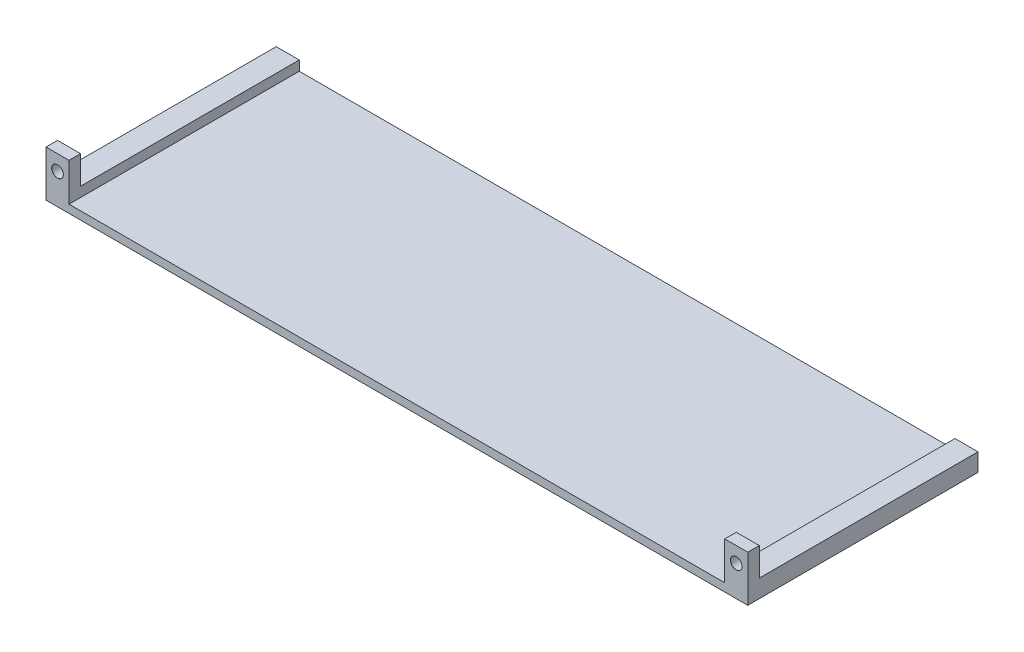
SolidWorks part; units mm, degrees
ref_plane "Front Plane" through (0, 0, 0) normal (0, 0, 1) x (1, 0, 0)
ref_plane "Top Plane" through (0, 0, 0) normal (0, 1, 0) x (1, 0, 0)
ref_plane "Right Plane" through (0, 0, 0) normal (1, 0, 0) x (0, 0, -1)
sketch "Sketch1" plane through (0, 0, 0) normal (0, 0, 1) x (1, 0, 0)
  line L0 (0, 0) -> (14.7224, 8.5)
  line L1 (0, 0) -> (0, -17)
  line L2 (0, 0) -> (-14.7224, 8.5)
  line L3 (0, 0) -> (0, -44.24)
  line L4 (-152.4, -44.24) -> (152.4, -44.24)
  line L5 (-152.4, -44.24) -> (-152.4, -24.8405)
  line L6 (0, -44.24) -> (0, -40.25)
  line L8 (-152.4, -44.24) -> (152.4, -44.24)
  line L9 (-152.4, -44.24) -> (-152.4, -40.74)
  line L10 (-152.4, -40.74) -> (152.4, -40.74)
  line L11 (152.4, -44.24) -> (152.4, -40.74)
  line L12 (-152.4, -40.74) -> (-142.4, -40.74)
  line L13 (-152.4, -40.74) -> (-152.4, -24.24)
  line L14 (-152.4, -24.24) -> (-142.4, -24.24)
  line L15 (-142.4, -40.74) -> (-142.4, -24.24)
  line L16 (152.4, -40.74) -> (142.4, -40.74)
  line L17 (152.4, -40.74) -> (152.4, -24.24)
  line L18 (152.4, -24.24) -> (142.4, -24.24)
  line L19 (142.4, -40.74) -> (142.4, -24.24)
  circle A0 centre (0, 0) radius 13.01
  circle A1 centre (0, 0) radius 17
  circle A2 centre (0, -17) radius 2.01
  circle A3 centre (14.7506, 8.5319) radius 2.01
  circle A4 centre (-14.9188, 8.588) radius 2.01
  circle A5 centre (0, 0) radius 40.25
  point P16 (0, -44.24)
  dimension "D1" = 26.02
  dimension "D2" = 34
  dimension "D3" = 4.02
  dimension "D8" = 80.5
  dimension "D4" = 120
  dimension "D5" = 120
  dimension "D6" = 44.24
  dimension "D7" = 304.8
  dimension "D9" = 3.5
  dimension "D10" = 10
  dimension "D11" = 10
  dimension "D12" = 16.5
  dimension "D13" = 16.5
extrude "Boss-Extrude1" add sketch "Sketch1" against normal blind 100 contours L10 L15 L14 L13 L5 | L10 L5 L4 L6 | L4 L11 L10 L6 | L19 L10 L17 L18
sketch "Sketch3" plane through (0, 0, 0) normal (0, 0, 1) x (1, 0, 0)
  line L0 (-142.4, -40.74) -> (-152.4, -40.74) construction
  line L1 (-152.4, -44.24) -> (-152.4, -24.24) construction
  line L2 (-142.4, -27.5127) -> (-152.4, -27.5127) construction
  line L3 (-142.4, -40.74) -> (-142.4, -24.24) construction
  line L4 (-147.4, -44.24) -> (-147.4, -37.5733)
  line L5 (-152.4, -44.24) -> (152.4, -44.24) construction
  line L6 (-147.4, -37.5733) -> (-147.4, -30.9067)
  line L7 (0, -40.25) -> (0, -44.24)
  line L8 (147.4, -44.24) -> (147.4, -37.5733)
  line L9 (147.4, -37.5733) -> (147.4, -30.9067)
  dimension "D1" = 6.6667
  dimension "D2" = 6.6667
hole_wizard "Ø5.0mm Dowel Hole3" positions "Sketch4" profile "Sketch6" hole size "Ø5.0" standard "ANSI Metric"
sketch "Sketch4" plane through (0, 0, 0) normal (0, 0, 1) x (1, 0, 0)
  point P0 (-147.4, -30.9067)
  point P3 (-147.4, -37.5733)
  point P6 (147.4, -30.9067)
  point P9 (147.4, -37.5733)
sketch "Sketch6" plane through (-147.4, -30.9067, 0) normal (1, 0, 0) x (0, -1, 0)
  line L0 (0, 0) -> (0, 101.5022)
  line L1 (0, 101.5022) -> (2.5, 100)
  line L2 (2.5, 100) -> (2.5, 0.025)
  line L3 (2.5, 0.025) -> (2.525, 0)
  line L5 (2.525, 0) -> (0, 0)
  line L6 (-2.5, 0.025) -> (-2.525, 0) construction
  line L10 (0, 101.5022) -> (-2.5, 100) construction
  line L11 (0, -6.35) -> (0, 107.95) construction
  dimension "Hole Dia." = 5
  dimension "Hole Depth" = 100
  dimension "Near C'Sink Dia." = 5.05
  dimension "Near C'Sink Angle" = 90
  dimension "Drill Angle" = 118
sketch "Sketch7" plane through (-152.4, 0, 0) normal (-1, 0, 0) x (0, 0, 1)
  line L0 (0, -35.74) -> (-5, -35.74)
  line L1 (0, -44.24) -> (0, -24.24) construction
  line L2 (-5, -35.74) -> (-5, -24.24)
  line L3 (-100, -24.24) -> (0, -24.24) construction
  line L4 (-100, -44.24) -> (0, -44.24) construction
  line L5 (-100, -44.24) -> (-100, -24.24) construction
  line L6 (-5, -24.24) -> (-100, -24.24)
  line L7 (-5, -24.24) -> (-5, -35.74)
  line L8 (-5, -35.74) -> (-100, -35.74)
  line L9 (-100, -24.24) -> (-100, -35.74)
  dimension "D1" = 5
  dimension "D2" = 8.5
sketch "Sketch8" plane through (0, 0, -100) normal (0, 0, -1) x (-1, 0, 0)
  circle A1 centre (147.4, -37.5733) radius 2.5
extrude "Boss-Extrude2" add sketch "Sketch8" against normal up to surface (100 mm away) up to face at (-144.875, -30.9067, 0)
sketch "Sketch11" plane through (0, 0, 0) normal (0, 0, 1) x (1, 0, 0)
  line L1 (-151.1194, -34.5462) -> (-143.5153, -34.5462)
  line L2 (-151.1194, -34.5462) -> (-151.1194, -40.8691)
  line L3 (-151.1194, -40.8691) -> (-143.5153, -40.8691)
  line L4 (-143.5153, -34.5462) -> (-143.5153, -40.8691)
extrude "Boss-Extrude3" add sketch "Sketch11" against normal blind 10
mirror "Mirror4" about plane through (0, 0, 0) normal (1, 0, 0) of "Boss-Extrude2"
sketch "Sketch10" plane through (152.4, 0, 0) normal (1, 0, 0) x (0, 0, -1)
  line L0 (0, -44.24) -> (0, -24.24) construction
  line L1 (100, -24.24) -> (5, -24.24)
  line L2 (100, -24.24) -> (100, -36.49)
  line L3 (100, -36.49) -> (5, -36.49)
  line L4 (5, -24.24) -> (5, -36.49)
  line L5 (100, -44.24) -> (0, -44.24) construction
  dimension "D1" = 5
  dimension "D2" = 7.75
extrude "Cut-Extrude3" cut sketch "Sketch10" against normal blind 10
mirror "Mirror5" about plane through (0, 0, 0) normal (1, 0, 0) of "Cut-Extrude3"
sketch "Sketch12" plane through (0, 0, 0) normal (0, 0, 1) x (1, 0, 0)
  line L1 (143.8975, -34.3719) -> (151.2172, -34.3719)
  line L2 (143.8975, -34.3719) -> (143.8975, -41.2156)
  line L3 (143.8975, -41.2156) -> (151.2172, -41.2156)
  line L4 (151.2172, -34.3719) -> (151.2172, -41.2156)
extrude "Boss-Extrude4" add sketch "Sketch12" against normal blind 5
equation "\"127.80063128mmftft\"=127.801"
